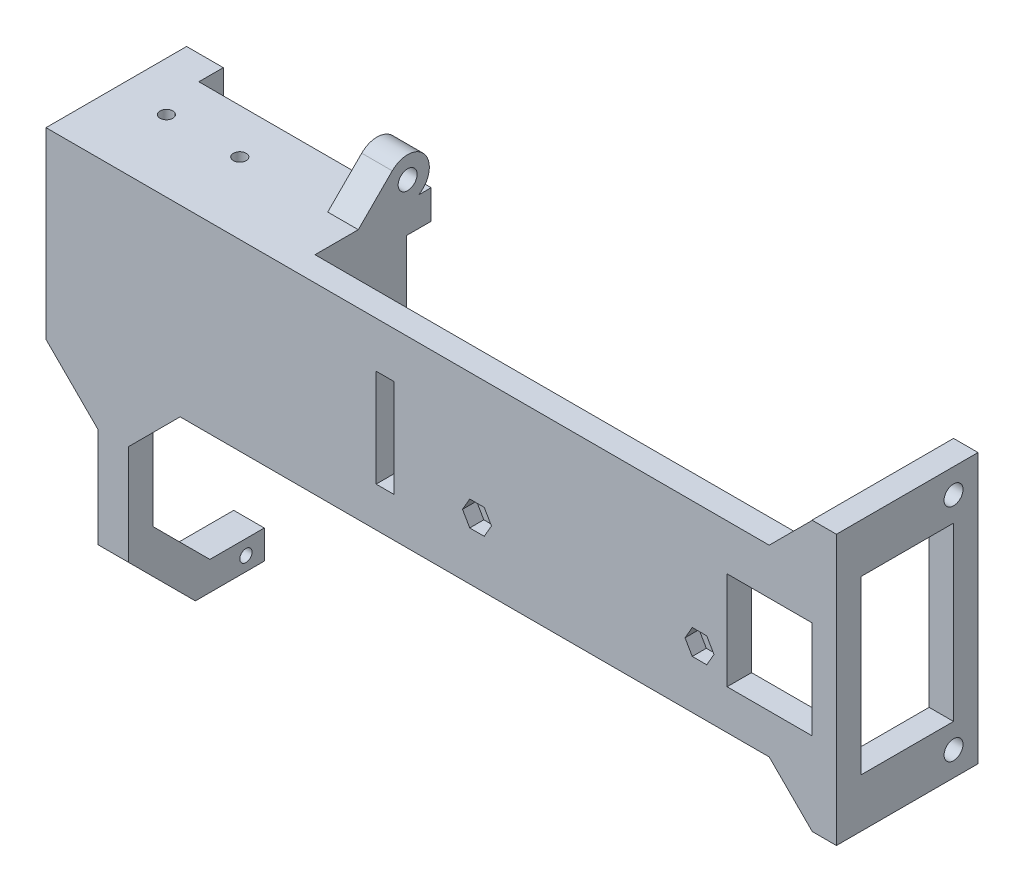
SolidWorks part; units mm, degrees
ref_plane "前视基准面" through (0, 0, 0) normal (0, 0, 1) x (1, 0, 0)
ref_plane "上视基准面" through (0, 0, 0) normal (0, 1, 0) x (1, 0, 0)
ref_plane "右视基准面" through (0, 0, 0) normal (1, 0, 0) x (0, 0, -1)
sketch "草图1" plane through (0, 0, 0) normal (0, 0, 1) x (1, 0, 0)
  line L0 (-29.15, 4.6184) -> (-29.15, -3.6184) construction
  line L1 (-84.15, 15.5) -> (-44.15, 15.5)
  line L2 (-84.15, 15.5) -> (-84.15, -14.5)
  line L3 (-84.15, -14.5) -> (-44.15, -14.5)
  line L4 (-44.15, 15.5) -> (-44.15, -14.5)
  line L6 (-99.2, 0.5) -> (-38.212, 0.5) construction
  line L7 (-99.2, 10.23) -> (-99.2, -9.23) construction
  dimension "D1" = 40
  dimension "D2" = 30
  dimension "D3" = 15
extrude "凸台-拉伸1" add sketch "草图1" against normal up to surface (15 mm away)
sketch "草图3" plane through (-44.15, 0, 0) normal (1, 0, 0) x (0, 0, -1)
  line L1 (21.7736, 17) -> (10.0505, 17) construction
  line L2 (15, 15.5) -> (0, 15.5) construction
  line L3 (15.155, 23.504) -> (15.155, 11.8832) construction
  line L4 (12.6448, 21.0602) -> (7.0845, 15.5)
  line L8 (15, 10.23) -> (15, -9.23)
  line L9 (15, -9.23) -> (15.31, -9.23)
  line L10 (15.31, -9.23) -> (15.31, 10.23)
  line L11 (15.31, 10.23) -> (15, 10.23)
  line L12 (15, 10.23) -> (15, -9.23) construction
  line L13 (15, -9.23) -> (15.31, -9.23) construction
  line L14 (15.31, -9.23) -> (15.31, 10.23) construction
  line L15 (15.31, 10.23) -> (15, 10.23) construction
  circle A0 centre (15.155, 18.55) radius 1.55
  circle A1 centre (15.155, 18.55) radius 3.55
  dimension "D1" = 3.1
  dimension "D2" = 2
  dimension "D3" = 1.5
  dimension "D5" = 45
  dimension "D4" = 0
extrude "凸台-拉伸2" add sketch "草图3" against normal blind 5
ref_plane "基准面-中间" through (0, 0.5, 0) normal (0, 1, 0) x (1, 0, 0)
mirror "镜向2" about plane through (0, 0.5, 0) normal (0, 1, 0) of "凸台-拉伸2"
sketch "草图4" plane through (0, 0, -15) normal (0, 0, -1) x (-1, 0, 0)
  line L0 (44.15, -14.0034) -> (44.15, 15.0034) construction
  line L1 (44.15, 10.73) -> (50.15, 10.73)
  line L2 (44.15, 10.73) -> (44.15, 15.5)
  line L3 (44.15, 15.5) -> (50.15, 15.5)
  line L4 (50.15, 10.73) -> (50.15, 15.5)
  line L5 (49.15, 15.5) -> (84.15, 15.5) construction
  line L6 (-18.5, 10.23) -> (-0.85, 10.23) construction
  line L7 (84.15, -14.5) -> (49.15, -14.5) construction
  line L8 (84.15, 15.5) -> (78.15, 15.5)
  line L9 (84.15, 15.5) -> (84.15, 10.73)
  line L10 (84.15, 10.73) -> (78.15, 10.73)
  line L11 (78.15, 15.5) -> (78.15, 10.73)
  line L12 (84.15, -14.5) -> (78.15, -14.5)
  line L13 (84.15, -14.5) -> (84.15, -9.73)
  line L14 (84.15, -9.73) -> (78.15, -9.73)
  line L15 (78.15, -14.5) -> (78.15, -9.73)
  line L16 (44.15, -9.73) -> (50.15, -9.73)
  line L17 (44.15, -9.73) -> (44.15, -14.5)
  line L18 (44.15, -14.5) -> (50.15, -14.5)
  line L19 (50.15, -9.73) -> (50.15, -14.5)
  line L20 (-18.5, -9.23) -> (-0.85, -9.23) construction
  line L21 (34.25, -9.23) -> (35.15, -9.23) construction
  line L22 (34.25, 10.23) -> (35.15, 10.23) construction
  dimension "D1" = 0.5
  dimension "D2" = 6
  dimension "D3" = 0.5
  dimension "D4" = 0.5
  dimension "D5" = 0.5
  dimension "D6" = 6
  dimension "D7" = 6
  dimension "D8" = 6
extrude "凸台-拉伸3" add sketch "草图4" along normal blind 4
sketch "草图5" plane through (0, 0, 0) normal (0, 0, 1) x (1, 0, 0)
  line L1 (-84.15, -14.5) -> (45.15, -14.5)
  line L2 (-84.15, -14.5) -> (-84.15, 15.5)
  line L3 (-84.15, 15.5) -> (45.15, 15.5)
  line L4 (45.15, -14.5) -> (45.15, 15.5)
  line L6 (40.15, -6.5) -> (40.15, 7.5) construction
  line L8 (41.15, -8) -> (27.2634, -8)
  line L9 (41.15, -8) -> (41.15, 8)
  line L10 (41.15, 8) -> (27.2634, 8)
  line L11 (27.2634, -8) -> (27.2634, 8)
  line L12 (-29.15, 4.6184) -> (-29.15, -3.6184) construction
  line L13 (-27.2634, -8) -> (-30.15, -8)
  line L14 (-27.2634, -8) -> (-27.2634, 8)
  line L15 (-27.2634, 8) -> (-30.15, 8)
  line L16 (-30.15, -8) -> (-30.15, 8)
  dimension "D1" = 5
  dimension "D2" = 1
  dimension "D3" = 1
extrude "凸台-拉伸4" add sketch "草图5" along normal blind 4
sketch "草图7" plane through (45.15, 0, 0) normal (1, 0, 0) x (0, 0, -1)
  line L0 (-4, -14.5) -> (-4, 15.5) construction
  line L1 (19.155, 22.55) -> (-4, 22.55)
  line L2 (19.155, 22.55) -> (19.155, 14.55)
  line L3 (19.155, 14.55) -> (-4, 14.55)
  line L4 (-4, 22.55) -> (-4, 14.55)
  line L5 (19.155, 22.55) -> (-4, 14.55) construction
  line L6 (19.155, 14.55) -> (-4, 22.55) construction
  line L8 (19.155, -21.55) -> (-4, -21.55)
  line L9 (19.155, -21.55) -> (19.155, -13.55)
  line L10 (19.155, -13.55) -> (-4, -13.55)
  line L11 (-4, -21.55) -> (-4, -13.55)
  line L12 (19.155, -21.55) -> (-4, -13.55) construction
  line L13 (19.155, -13.55) -> (-4, -21.55) construction
  line L14 (19.155, 14.55) -> (15.155, 14.55)
  line L15 (19.155, 14.55) -> (19.155, -13.55)
  line L16 (19.155, -13.55) -> (15.155, -13.55)
  line L17 (15.155, 14.55) -> (15.155, -13.55)
  circle A0 centre (15.155, 18.55) radius 1.55
  circle A1 centre (15.155, -17.55) radius 1.55
  arc A2 (16.9716, 15.5) -> (12.6448, 21.0602) centre (15.155, 18.55) ccw construction
  arc A3 (12.6448, -20.0602) -> (16.9716, -14.5) centre (15.155, -17.55) ccw construction
  point P10 (7.5775, 18.55)
  point P17 (7.5775, -17.55)
  line M11 (0, -14.5) -> (0, 15.5)
  line M12 (0, 15.5) -> (-4, 15.5)
  line M13 (-4, 15.5) -> (-4, -14.5)
  line M14 (-4, -14.5) -> (0, -14.5)
  dimension "D1" = 3.1
  dimension "D3" = 4
  dimension "D4" = 4
  dimension "D5" = 4
  dimension "D6" = 4
extrude "凸台-拉伸5" add sketch "草图7" against normal blind 4 contours L11 L8 L9 L10 A1 M11 M14 | L10 M11 M13 M14 | L3 L17 L10 L16 L15 | L1 L4 L3 L2 A0 M12 M11
sketch "草图8" plane through (-75.6797, 0, 0) normal (1, 0, 0) x (0, 0, -1)
  line L0 (21.135, -23.0958) -> (9.335, -23.0958) construction
  line L1 (18.235, -23.0958) -> (12.235, -23.0958)
  line L2 (18.235, -23.0958) -> (18.235, -14.5)
  line L3 (18.235, -14.5) -> (12.235, -14.5)
  line L4 (12.235, -23.0958) -> (12.235, -14.5)
  line L5 (19, -14.5) -> (-4, -14.5) construction
  line L6 (13.3924, -23.0958) -> (4.7966, -14.5)
  line L7 (18.235, -19.4531) -> (13.2819, -14.5)
  line L8 (15.885, -18.3958) -> (21.135, -18.3958) construction
  line L9 (4.7966, -14.5) -> (12.235, -14.5)
  arc A0 (14.585, -19.9358) -> (15.885, -19.9358) centre (15.235, -20.6958) ccw construction
  circle A1 centre (15.235, -20.6958) radius 1
  line M7 (21.135, -18.3958) -> (15.885, -18.3958)
  line M8 (15.885, -18.3958) -> (15.885, -19.9358)
  arc M9 (15.885, -19.9358) -> (14.585, -19.9358) centre (15.235, -20.6958) cw
  line M10 (14.585, -19.9358) -> (14.585, -18.3958)
  line M11 (14.585, -18.3958) -> (9.335, -18.3958)
  line M12 (9.335, -18.3958) -> (9.335, -23.0958)
  dimension "D1" = 3
  dimension "D5" = 3
  dimension "D6" = 3
  dimension "D2" = 3
  dimension "D3" = 45
  dimension "D4" = 45
extrude "凸台-拉伸6" add sketch "草图8" along normal blind 5 contours L9 L6 L4 M12 M11 | L6 L4 M11 M12 | L6 L1 L2 L4 M7 M8 M9 M10 M11 | L7 L3 L4 M7 M11 M10 M9 M8
sketch "草图9" plane through (-75.6797, 0, 0) normal (1, 0, 0) x (0, 0, -1)
  line L0 (9.335, -50.2958) -> (6.9639, -50.2958)
  line L1 (21.135, -45.5958) -> (9.335, -45.5958) construction
  line L2 (18.235, -45.5958) -> (9.335, -45.5958)
  line L3 (18.235, -45.5958) -> (18.235, -50.2958)
  line L4 (18.235, -50.2958) -> (9.335, -50.2958)
  line L5 (9.335, -45.5958) -> (9.335, -50.2958)
  line L6 (18.235, -23.0958) -> (18.235, -19.4531) construction
  line L7 (9.335, -45.5958) -> (-4, -32.2608)
  line L8 (6.9639, -50.2958) -> (-4, -39.3318)
  line L10 (-4, -39.3318) -> (-4, -32.2608)
  line L11 (9.335, -23.0958) -> (9.335, -45.5958) construction
  line L12 (-4, 15.5) -> (-4, -14.5) construction
  arc A0 (15.885, -48.7557) -> (14.585, -48.7557) centre (15.235, -47.9958) ccw construction
  circle A1 centre (15.235, -47.9958) radius 1
  line M5 (9.335, -50.2958) -> (14.585, -50.2958)
  line M6 (14.585, -50.2958) -> (14.585, -48.7557)
  arc M7 (14.585, -48.7557) -> (15.885, -48.7557) centre (15.235, -47.9958) cw
  line M8 (15.885, -48.7557) -> (15.885, -50.2958)
  line M9 (15.885, -50.2958) -> (21.135, -50.2958)
  line M11 (21.135, -45.5958) -> (9.335, -45.5958)
  line M12 (9.335, -45.5958) -> (9.335, -50.2958)
  dimension "D1" = 45
  dimension "D2" = 5
extrude "凸台-拉伸7" add sketch "草图9" along normal blind 5 separate body contours L10 L8 L0 L7 M12 | L3 M11 M12 M5 M6 M7 M8 M9 | A1 L4 M6 M8
sketch "草图11" plane through (0, 0, 4) normal (0, 0, 1) x (1, 0, 0)
  line L0 (-70.6797, -39.3318) -> (-70.6797, -22.9703)
  line L2 (-84.15, -14.5) -> (-75.6797, -22.9703)
  line L3 (-75.6797, -22.9703) -> (-75.6797, -39.3318)
  line L5 (-70.6797, -22.9703) -> (-62.2093, -14.5)
  line L6 (-84.15, -14.5) -> (41.15, -14.5) construction
  line L9 (-62.2093, -14.5) -> (-84.15, -14.5)
  line L10 (-75.6797, -39.3318) -> (-70.6797, -39.3318)
  line L11 (-75.6797, -39.3318) -> (-75.6797, -32.2608) construction
  dimension "D1" = 45
  dimension "D2" = 45
extrude "凸台-拉伸8" add sketch "草图11" against normal blind 4
sketch "草图12" plane through (0, 15.5, 0) normal (0, 1, 0) x (1, 0, 0)
  circle A0 centre (-76.15, 7.7) radius 1.05
  circle A1 centre (-64.15, 7.7) radius 1.05
  dimension "D1" = 2.1
extrude "切除-拉伸1" cut sketch "草图12" against normal blind 9
sketch "草图13" plane through (0, -14.5, 0) normal (0, -1, 0) x (1, 0, 0)
  circle A0 centre (-64.15, -7.7) radius 1.05
  circle A1 centre (-79.6527, -7.7) radius 1.05
  dimension "D1" = 2.1
extrude "切除-拉伸2" cut sketch "草图13" against normal blind 9
chamfer "倒角1" distance 7 angle 45 2 edges at (41.15, 15.5, 2) (41.15, -14.5, 2)
sketch "草图14" plane through (0, 0, 0) normal (0, 0, -1) x (-1, 0, 0)
  circle A0 centre (-22.75, -4.5) radius 1
  circle A1 centre (13.65, -4.5) radius 1
  dimension "D1" = 2
extrude "切除-拉伸3" cut sketch "草图14" against normal up to next
sketch "草图15" plane through (0, 0, 0) normal (0, 0, -1) x (-1, 0, 0)
  line L1 (17.5489, -3.55) -> (19.3958, -3.55) construction
  line L2 (17.4871, -3.5) -> (19.0529, -3.5) construction
  circle A1 centre (18.27, -4.5) radius 0.95
  circle A2 centre (-18.1, -4.5) radius 0.95
  circle A3 centre (-18.1, -4.5) radius 0.95
  arc A4 (19.0529, -5.5) -> (19.0529, -3.5) centre (18.27, -4.5) ccw construction
  arc A5 (17.4871, -3.5) -> (17.4871, -5.5) centre (18.27, -4.5) ccw construction
  dimension "D2" = 0.05
  dimension "D1" = 0.05
extrude "凸台-拉伸9" add sketch "草图15" along normal blind 1
fillet "圆角1" radius 0.5 2 edges at (-19.22, -4.5, -1) (17.15, -4.5, -1)
sketch "草图16" plane through (0, 0, 4) normal (0, 0, 1) x (1, 0, 0)
  line L1 (25.1171, -4.5) -> (23.9336, -2.45)
  line L2 (23.9336, -2.45) -> (21.5664, -2.45)
  line L3 (21.5664, -2.45) -> (20.3829, -4.5)
  line L4 (20.3829, -4.5) -> (21.5664, -6.55)
  line L5 (21.5664, -6.55) -> (23.9336, -6.55)
  line L6 (23.9336, -6.55) -> (25.1171, -4.5)
  line L7 (-11.2829, -4.5) -> (-12.4664, -2.45)
  line L8 (-12.4664, -2.45) -> (-14.8336, -2.45)
  line L9 (-14.8336, -2.45) -> (-16.0171, -4.5)
  line L10 (-16.0171, -4.5) -> (-14.8336, -6.55)
  line L11 (-14.8336, -6.55) -> (-12.4664, -6.55)
  line L12 (-12.4664, -6.55) -> (-11.2829, -4.5)
  circle A0 centre (22.75, -4.5) radius 2.05 construction
  circle A1 centre (-13.65, -4.5) radius 2.05 construction
  dimension "D1" = 4.1
extrude "切除-拉伸4" cut sketch "草图16" against normal blind 2.3
